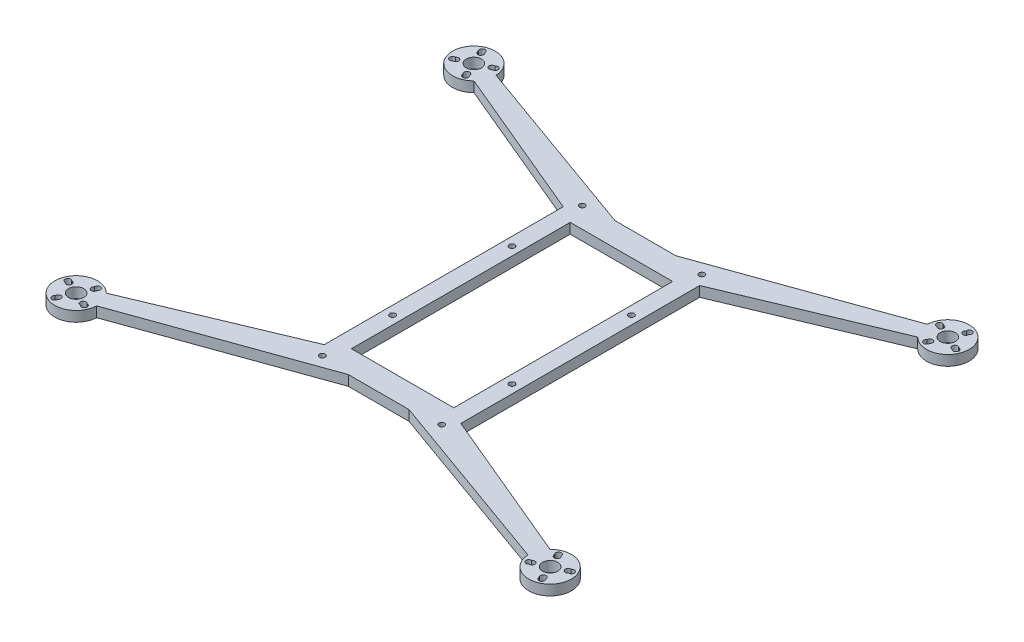
SolidWorks part; units mm, degrees
ref_plane "Спереди" through (0, 0, 0) normal (0, 0, 1) x (1, 0, 0)
ref_plane "Сверху" through (0, 0, 0) normal (0, 1, 0) x (1, 0, 0)
ref_plane "Справа" through (0, 0, 0) normal (1, 0, 0) x (0, 0, -1)
sketch "Эскиз1" plane through (0, 0, 0) normal (0, 1, 0) x (1, 0, 0)
  line L0 (-1001.6092, 0) -> (48998.3908, 0) construction
  line L1 (0, -1000) -> (0, 49000) construction
  line L2 (138.9, 116.5509) -> (-138.9, -116.5509) construction
  line L3 (-138.9, 116.5509) -> (138.9, -116.5509) construction
  line L4 (-50, -934.8861) -> (-50, 49065.1139) construction
  line L5 (-17.7777, 78.1295) -> (17.7777, 78.1295)
  line L6 (-40, 70) -> (-40, -70)
  line L7 (-17.7777, -78.1295) -> (17.7777, -78.1295)
  line L8 (40, 70) -> (40, -70)
  line L9 (50, -952.4142) -> (50, 49047.5858) construction
  line L10 (-138.9, 116.5509) -> (-40, 78.1295) construction
  line L11 (-30, 64.1295) -> (30, 64.1295)
  line L12 (-30, 64.1295) -> (-30, -64.1295)
  line L13 (-30, -64.1295) -> (30, -64.1295)
  line L14 (30, 64.1295) -> (30, -64.1295)
  line L15 (-126.4105, 117.063) -> (-17.7777, 78.1295)
  line L16 (-130.0317, 107.7417) -> (-40, 70)
  line L18 (-130.0317, -107.7417) -> (-40, -70)
  line L19 (-126.4105, -117.063) -> (-17.7777, -78.1295)
  line L20 (126.4105, -117.063) -> (17.7777, -78.1295)
  line L22 (130.0317, -107.7417) -> (40, -70)
  line L24 (130.0317, 107.7417) -> (40, 70)
  line L25 (126.4105, 117.063) -> (17.7777, 78.1295)
  line L26 (-37.2841, 85.1205) -> (-42.7159, 71.1385) construction
  line L27 (-40, 78.1295) -> (-17.7777, 78.1295) construction
  line L28 (-40, 78.1295) -> (-40, 70) construction
  line L29 (40, 78.1295) -> (40, 70) construction
  line L30 (40, 78.1295) -> (17.7777, 78.1295) construction
  line L31 (-40, -78.1295) -> (-40, -70) construction
  line L32 (-40, -78.1295) -> (-17.7777, -78.1295) construction
  line L33 (40, -78.1295) -> (40, -70) construction
  line L34 (40, -78.1295) -> (17.7777, -78.1295) construction
  circle A0 centre (-138.9, 116.5509) radius 88.9 construction
  circle A1 centre (138.9, 116.5509) radius 88.9 construction
  circle A2 centre (138.9, -116.5509) radius 88.9 construction
  circle A3 centre (-138.9, -116.5509) radius 88.9 construction
  arc A4 (-126.4105, 117.063) -> (-130.0317, 107.7417) centre (-138.9, 116.5509) ccw
  arc A5 (126.4105, 117.063) -> (130.0317, 107.7417) centre (138.9, 116.5509) cw
  arc A6 (126.4105, -117.063) -> (130.0317, -107.7417) centre (138.9, -116.5509) ccw
  arc A7 (-126.4105, -117.063) -> (-130.0317, -107.7417) centre (-138.9, -116.5509) cw
  point P14 (0, 0)
  dimension "D3" = 177.8
  dimension "D5" = 25
  dimension "D1" = 80
  dimension "D2" = 80
  dimension "D4" = 100
  dimension "D6" = 14
  dimension "D7" = 10
  dimension "D8" = 10
  dimension "D9" = 140
  dimension "D10" = 15
extrude "Бобышка-Вытянуть1" add sketch "Эскиз1" along normal mid plane 6
sketch "Эскиз2" plane through (0, 3, 0) normal (0, 1, 0) x (1, 0, 0)
  line L0 (-138.9, 116.5509) -> (-40, 78.1295) construction
  line L1 (-127.4603, 121.5892) -> (-150.3397, 111.5127) construction
  line L2 (-143.9382, 127.9906) -> (-133.8618, 105.1113) construction
  line L3 (-1000, 0) -> (49000, 0) construction
  line L4 (0, -1000) -> (0, 49000) construction
  line L5 (143.9382, 127.9906) -> (133.8618, 105.1113) construction
  line L6 (127.4603, 121.5892) -> (150.3397, 111.5127) construction
  line L7 (127.4603, -121.5892) -> (150.3397, -111.5127) construction
  line L8 (143.9382, -127.9906) -> (133.8618, -105.1113) construction
  line L9 (-143.9382, -127.9906) -> (-133.8618, -105.1113) construction
  line L10 (-127.4603, -121.5892) -> (-150.3397, -111.5127) construction
  circle A0 centre (-138.9, 116.5509) radius 9.5 construction
  circle A1 centre (-138.9, 116.5509) radius 8 construction
  circle A2 centre (-138.9, 116.5509) radius 4.5
  arc A3 (-126.4105, 117.063) -> (-130.0317, 107.7417) centre (-138.9, 116.5509) ccw construction
  arc A4 (-141.0817, 125.1511) -> (-143.7718, 123.9663) centre (-142.729, 125.2451) ccw
  arc A6 (-143.7718, 123.9663) -> (-141.0817, 125.1511) centre (-142.1245, 123.8723) ccw
  arc A7 (-130.2999, 118.7327) -> (-131.4846, 121.4227) centre (-130.2058, 120.38) ccw
  arc A8 (-131.4846, 121.4227) -> (-130.2999, 118.7327) centre (-131.5786, 119.7754) ccw
  arc A9 (-136.7183, 107.9508) -> (-134.0282, 109.1355) centre (-135.071, 107.8568) ccw
  arc A10 (-134.0282, 109.1355) -> (-136.7183, 107.9508) centre (-135.6755, 109.2295) ccw
  arc A11 (-147.5001, 114.3692) -> (-146.3154, 111.6792) centre (-147.5942, 112.7219) ccw
  arc A12 (-146.3154, 111.6792) -> (-147.5001, 114.3692) centre (-146.2214, 113.3265) ccw
  circle A13 centre (138.9, 116.5509) radius 8 construction
  circle A14 centre (138.9, 116.5509) radius 9.5 construction
  arc A15 (146.3154, 111.6792) -> (147.5001, 114.3692) centre (146.2214, 113.3265) cw
  arc A16 (147.5001, 114.3692) -> (146.3154, 111.6792) centre (147.5942, 112.7219) cw
  arc A17 (134.0282, 109.1355) -> (136.7183, 107.9508) centre (135.6755, 109.2295) cw
  arc A18 (136.7183, 107.9508) -> (134.0282, 109.1355) centre (135.071, 107.8568) cw
  arc A19 (131.4846, 121.4227) -> (130.2999, 118.7327) centre (131.5786, 119.7754) cw
  arc A20 (130.2999, 118.7327) -> (131.4846, 121.4227) centre (130.2058, 120.38) cw
  arc A21 (143.7718, 123.9663) -> (141.0817, 125.1511) centre (142.1245, 123.8723) cw
  arc A22 (141.0817, 125.1511) -> (143.7718, 123.9663) centre (142.729, 125.2451) cw
  circle A23 centre (138.9, 116.5509) radius 4.5
  circle A24 centre (138.9, -116.5509) radius 9.5 construction
  circle A25 centre (138.9, -116.5509) radius 8 construction
  circle A26 centre (-138.9, -116.5509) radius 8 construction
  circle A27 centre (-138.9, -116.5509) radius 9.5 construction
  circle A28 centre (138.9, -116.5509) radius 4.5
  arc A29 (141.0817, -125.1511) -> (143.7718, -123.9663) centre (142.729, -125.2451) ccw
  arc A30 (143.7718, -123.9663) -> (141.0817, -125.1511) centre (142.1245, -123.8723) ccw
  arc A31 (130.2999, -118.7327) -> (131.4846, -121.4227) centre (130.2058, -120.38) ccw
  arc A32 (131.4846, -121.4227) -> (130.2999, -118.7327) centre (131.5786, -119.7754) ccw
  arc A33 (136.7183, -107.9508) -> (134.0282, -109.1355) centre (135.071, -107.8568) ccw
  arc A34 (134.0282, -109.1355) -> (136.7183, -107.9508) centre (135.6755, -109.2295) ccw
  arc A35 (147.5001, -114.3692) -> (146.3154, -111.6792) centre (147.5942, -112.7219) ccw
  arc A36 (146.3154, -111.6792) -> (147.5001, -114.3692) centre (146.2214, -113.3265) ccw
  arc A37 (-146.3154, -111.6792) -> (-147.5001, -114.3692) centre (-146.2214, -113.3265) cw
  arc A38 (-147.5001, -114.3692) -> (-146.3154, -111.6792) centre (-147.5942, -112.7219) cw
  arc A39 (-134.0282, -109.1355) -> (-136.7183, -107.9508) centre (-135.6755, -109.2295) cw
  arc A40 (-136.7183, -107.9508) -> (-134.0282, -109.1355) centre (-135.071, -107.8568) cw
  arc A41 (-131.4846, -121.4227) -> (-130.2999, -118.7327) centre (-131.5786, -119.7754) cw
  arc A42 (-130.2999, -118.7327) -> (-131.4846, -121.4227) centre (-130.2058, -120.38) cw
  arc A43 (-143.7718, -123.9663) -> (-141.0817, -125.1511) centre (-142.1245, -123.8723) cw
  arc A44 (-141.0817, -125.1511) -> (-143.7718, -123.9663) centre (-142.729, -125.2451) cw
  circle A45 centre (-138.9, -116.5509) radius 4.5
  point P12 (-142.729, 125.2451)
  point P13 (-142.1245, 123.8723)
  point P14 (-138.9, 116.5509)
  point P37 (-138.9, 116.5509)
  point P64 (138.9, 116.5509)
  point P65 (138.9, 116.5509)
  point P66 (142.1245, 123.8723)
  point P67 (142.729, 125.2451)
  point P116 (142.729, -125.2451)
  point P117 (142.1245, -123.8723)
  point P118 (138.9, -116.5509)
  point P119 (138.9, -116.5509)
  point P120 (-138.9, -116.5509)
  point P121 (-138.9, -116.5509)
  point P122 (-142.1245, -123.8723)
  point P123 (-142.729, -125.2451)
  dimension "D1" = 19
  dimension "D2" = 16
  dimension "D3" = 9
  dimension "D4" = 3.3
  dimension "D5" = 4
extrude "Вырез-Вытянуть1" cut sketch "Эскиз2" against normal through all
sketch "Эскиз3" plane through (0, 3, 0) normal (0, 1, 0) x (1, 0, 0)
  line L0 (-1000, 0) -> (49000, 0) construction
  line L1 (0, -1000) -> (0, 49000) construction
  line L2 (-40, 35) -> (-30, 35) construction
  line L3 (-40, 70) -> (-40, -70) construction
  line L4 (-30, 64.1295) -> (-30, -64.1295) construction
  circle A0 centre (-35, 76.19) radius 1.65
  circle A1 centre (-35, 35) radius 1.65
  circle A2 centre (-35, -35) radius 1.65
  circle A3 centre (-35, -76.19) radius 1.65
  circle A4 centre (35, -76.19) radius 1.65
  circle A5 centre (35, -35) radius 1.65
  circle A6 centre (35, 35) radius 1.65
  circle A7 centre (35, 76.19) radius 1.65
  point P29 (-35, 35)
  point P30 (0, 0)
  point P31 (0, 0)
  point P32 (-30, 5.8787)
  dimension "D1" = 3.3
  dimension "D2" = 76.19
  dimension "D3" = 35
extrude "Вырез-Вытянуть2" cut sketch "Эскиз3" against normal through all
